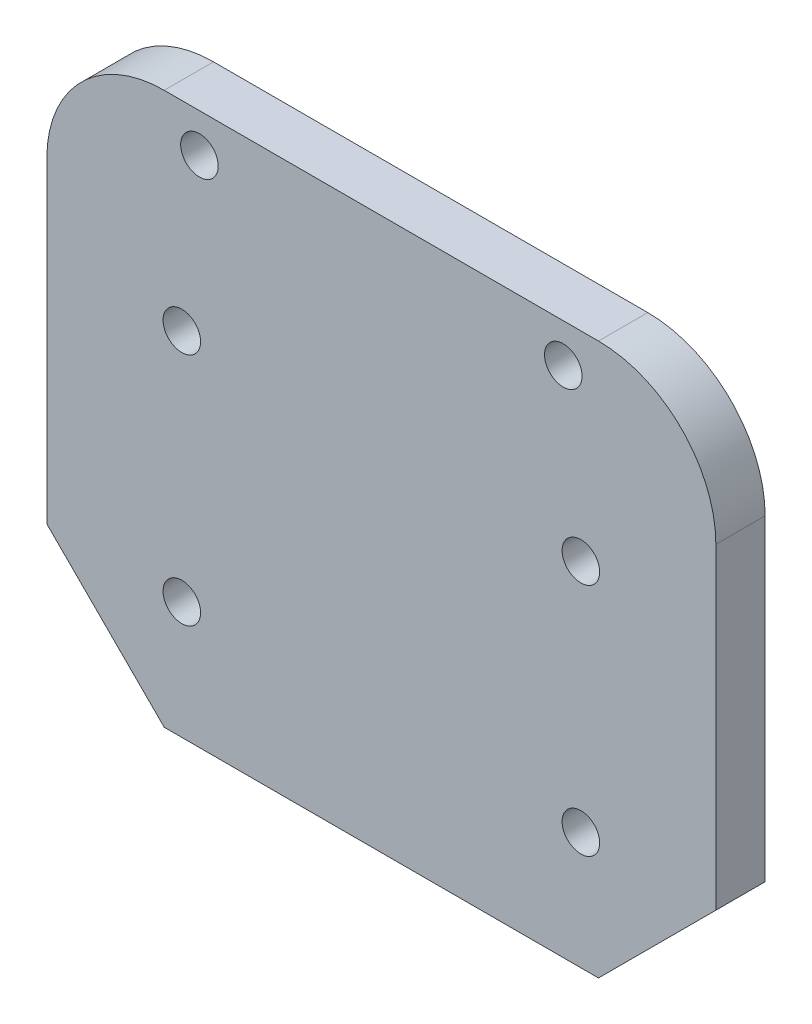
SolidWorks part; units mm, degrees
ref_plane "Front Plane" through (0, 0, 0) normal (1, 0, 0) x (0, 1, 0)
ref_plane "Top Plane" through (0, 0, 0) normal (0, 0, 1) x (0, 1, 0)
ref_plane "Right Plane" through (0, 0, 0) normal (0, 1, 0) x (-1, 0, 0)
sketch "Sketch2" plane through (0, 0, 0) normal (0, 0, 1) x (0, 1, 0)
  line L0 (47, 28.5) -> (0, 28.5) construction
  line L1 (0, 0) -> (37, 0)
  line L2 (0, 0) -> (0, 57)
  line L3 (0, 57) -> (37, 57)
  line L4 (47, 10) -> (47, 47)
  line L5 (43.7, 44) -> (43.7, 28.5) construction
  line L6 (43.7, 28.5) -> (43.7, 13) construction
  line L7 (10, 45.5) -> (30, 45.5) construction
  line L8 (30, 45.5) -> (30, 11.5) construction
  line L9 (30, 11.5) -> (10, 11.5) construction
  line L10 (10, 11.5) -> (10, 45.5) construction
  circle A0 centre (43.7, 44) radius 1.6
  circle A1 centre (43.7, 13) radius 1.6
  arc A2 (37, 0) -> (47, 10) centre (37, 10) ccw
  arc A3 (37, 57) -> (47, 47) centre (37, 47) cw
  circle A4 centre (10, 45.5) radius 1.6
  circle A5 centre (10, 11.5) radius 1.6
  circle A6 centre (30, 45.5) radius 1.6
  circle A7 centre (30, 11.5) radius 1.6
  point P13 (47, 57)
  point P25 (30, 28.5)
  point P26 (5.8665, 11.5)
  dimension "D3" = 10
  dimension "D10" = 3.2
  dimension "D1" = 57
  dimension "D2" = 47
  dimension "D4" = 3.3
  dimension "D5" = 31
  dimension "D6" = 34
  dimension "D7" = 20
  dimension "D8" = 10
extrude "Boss-Extrude1" add sketch "Sketch2" along normal blind 4.2
chamfer "Chamfer1" distance 10 angle 45 2 edges at (0, 0, 2.1) (-57, 0, 2.1)
